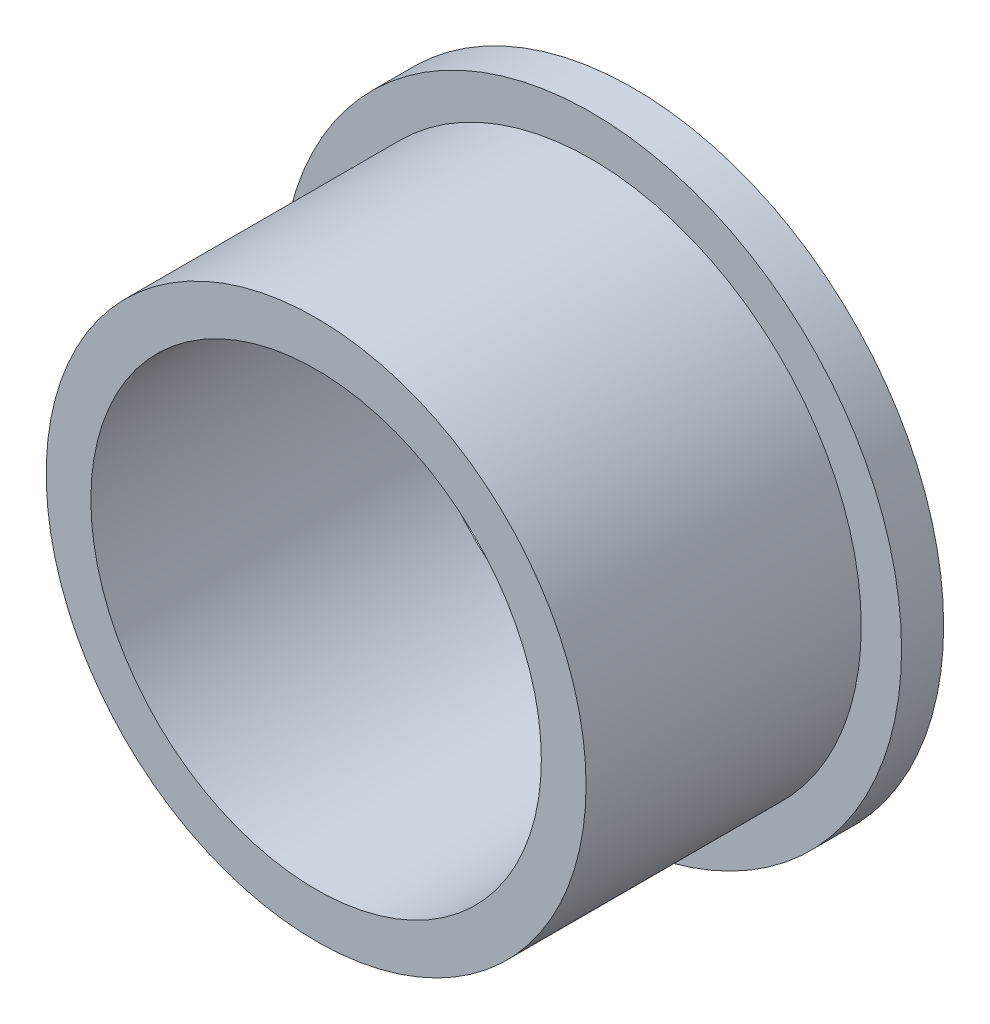
SolidWorks part; units mm, degrees
ref_plane "Ön Düzlem" through (0, 0, 0) normal (0, 0, 1) x (1, 0, 0)
ref_plane "Üst Düzlem" through (0, 0, 0) normal (0, 1, 0) x (1, 0, 0)
ref_plane "Sağ Düzlem" through (0, 0, 0) normal (1, 0, 0) x (0, 0, -1)
sketch "Çizim1" plane through (0, 0, 0) normal (0, 0, 1) x (1, 0, 0)
  circle A0 centre (0, 0) radius 17.7
  dimension "D1" = 35.4
extrude "Yükseklik-Ekstrüzyon1" add sketch "Çizim1" along normal blind 2.4
sketch "Çizim2" plane through (0, 0, 2.4) normal (0, 0, 1) x (1, 0, 0)
  circle A0 centre (0, 0) radius 15.4
  dimension "D1" = 30.8
extrude "Yükseklik-Ekstrüzyon2" add sketch "Çizim2" along normal blind 15.7
sketch "Çizim3" plane through (0, 0, 18.1) normal (0, 0, 1) x (1, 0, 0)
  circle A0 centre (0, 0) radius 12.85
  dimension "D1" = 25.7
extrude "Kes-Ekstrüzyon1" cut sketch "Çizim3" against normal blind 20
